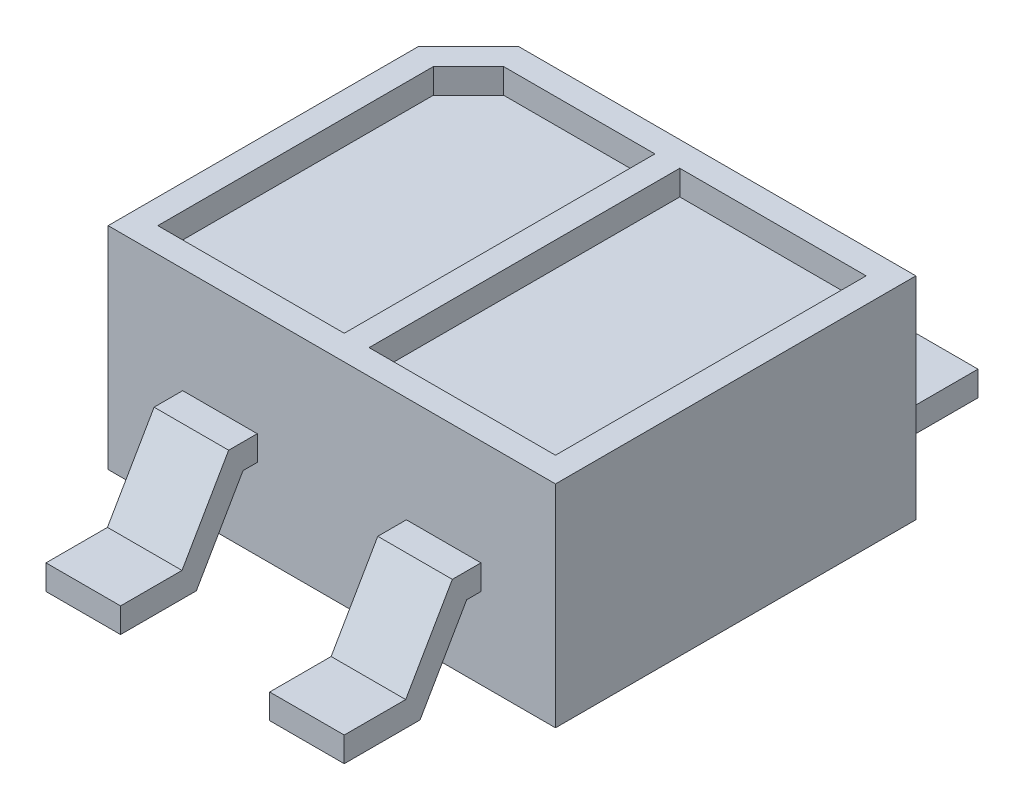
SolidWorks part; units mm, degrees
ref_plane "Front Plane" through (0, 0, 0) normal (0, 0, 1) x (1, 0, 0)
ref_plane "Top Plane" through (0, 0, 0) normal (0, 1, 0) x (1, 0, 0)
ref_plane "Right Plane" through (0, 0, 0) normal (1, 0, 0) x (0, 0, -1)
sketch "Sketch1" plane through (0, 0, 0) normal (0, 1, 0) x (1, 0, 0)
  line L0 (-3.2, 2.9) -> (-3.6, 2.5)
  line L1 (0, 0) -> (-3.6, 0)
  line L2 (0, 0) -> (0, 2.9)
  line L3 (0, 2.9) -> (-3.2, 2.9)
  line L4 (-3.6, 0) -> (-3.6, 2.5)
  dimension "D1" = 2.9
  dimension "D2" = 3.6
  dimension "D3" = 0.4
  dimension "D4" = 45
extrude "Base" add sketch "Sketch1" along normal blind 1.7
sketch "Sketch2" plane through (0, 1.7, 0) normal (0, 1, 0) x (1, 0, 0)
  line L0 (-0.2, 0.2) -> (-0.2, 2.7)
  line L1 (-0.2, 2.7) -> (-1.7, 2.7)
  line L2 (-1.7, 2.7) -> (-1.7, 0.2)
  line L3 (-1.7, 0.2) -> (-0.2, 0.2)
  line L4 (-1.9, 0.2) -> (-1.9, 2.7)
  line L5 (-1.9, 2.7) -> (-3.1172, 2.7)
  line L6 (-3.1172, 2.7) -> (-3.4, 2.4172)
  line L7 (-3.4, 2.4172) -> (-3.4, 0.2)
  line L8 (-3.4, 0.2) -> (-1.9, 0.2)
  line L9 (0, 0) -> (0, 2.9) construction
  line L10 (-3.6, 0) -> (0, 0) construction
  line L11 (-3.2, 2.9) -> (-3.6, 2.5) construction
  line L12 (-3.6, 2.5) -> (-3.6, 0) construction
  line L13 (0, 2.9) -> (-3.2, 2.9) construction
  line L14 (-3.2, 2.9) -> (-3.6, 2.5) construction
  point P13 (-3.4, 2.7)
  dimension "D1" = 0.2
  dimension "D2" = 0.2
  dimension "D3" = 0.2
  dimension "D4" = 0.2
  dimension "D5" = 0.2
  dimension "D6" = 0.2
extrude "Sensor Indents" cut sketch "Sketch2" against normal blind 0.2
ref_plane "Foot Plane" through (-0.9, 0, 0) normal (1, 0, 0) x (0, 0, -1)
sketch "Sketch3" plane through (-0.9, 0, 0) normal (1, 0, 0) x (0, 0, -1)
  line L0 (-1.1, 0) -> (-0.49, 0)
  line L1 (-0.49, 0) -> (-0.1147, 0.65)
  line L2 (-0.1147, 0.65) -> (0, 0.65)
  line L3 (0, 1.7) -> (0, 0) construction
  line L4 (0, 0.65) -> (0, 0.85)
  line L5 (0, 0.85) -> (-0.2302, 0.85)
  line L6 (-0.2302, 0.85) -> (-0.6055, 0.2)
  line L7 (-0.6055, 0.2) -> (-1.1, 0.2)
  line L8 (-1.1, 0.2) -> (-1.1, 0)
  dimension "D1" = 0.61
  dimension "D2" = 30
  dimension "D3" = 1.1
  dimension "D4" = 0.2
  dimension "D5" = 0.2
  dimension "D6" = 0.2
extrude "Foot" add sketch "Sketch3" along normal mid plane 0.6
pattern_linear "Feet" count 2 spacing 1.8 along (-1, 0, 0) of "Foot"
ref_plane "Mirror Plane" through (0, 0, -1.45) normal (0, 0, 1) x (1, 0, 0)
mirror "Feets" about plane through (0, 0, -1.45) normal (0, 0, 1) of "Feet", "Foot"
